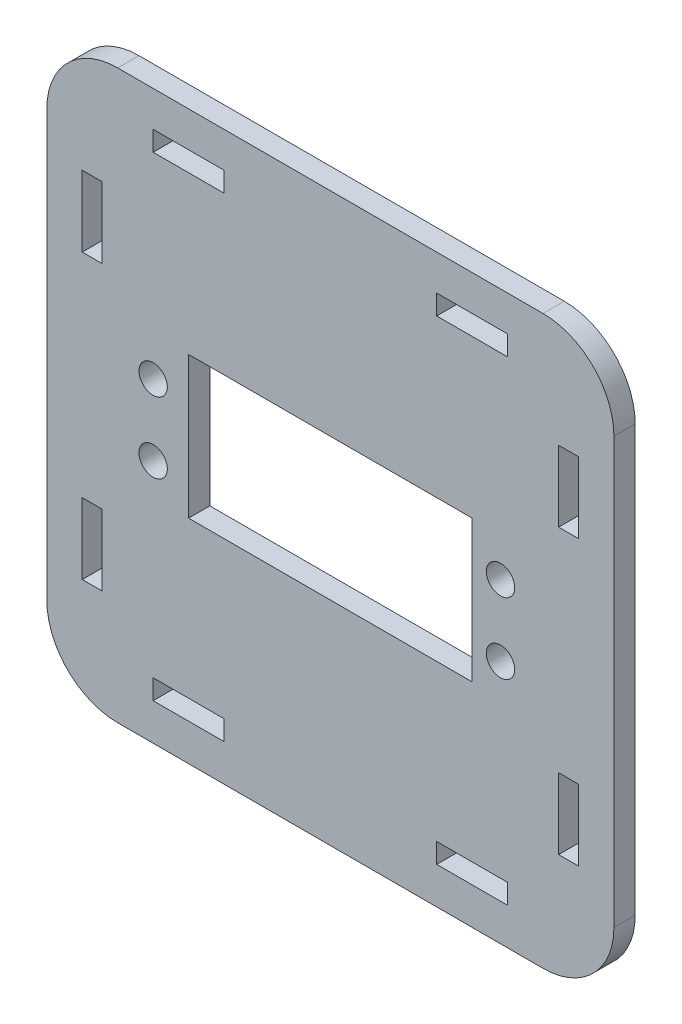
SolidWorks part; units mm, degrees
ref_plane "Plan de face" through (0, 0, 0) normal (0, 0, 1) x (1, 0, 0)
ref_plane "Plan de dessus" through (0, 0, 0) normal (0, 1, 0) x (1, 0, 0)
ref_plane "Plan de droite" through (0, 0, 0) normal (1, 0, 0) x (0, 0, -1)
sketch "Esquisse2" plane through (0, 0, 0) normal (0, 0, 1) x (1, 0, 0)
  line L1 (10, 0) -> (70, 0)
  line L2 (0, 10) -> (0, 70)
  line L3 (10, 80) -> (70, 80)
  line L4 (80, 10) -> (80, 70)
  arc A0 (70, 0) -> (80, 10) centre (70, 10) ccw
  arc A1 (10, 0) -> (0, 10) centre (10, 10) cw
  arc A2 (0, 70) -> (10, 80) centre (10, 70) cw
  arc A3 (70, 80) -> (80, 70) centre (70, 70) cw
  point P11 (0, 0)
  point P14 (0, 80)
  point P17 (80, 80)
  dimension "D3" = 10
  dimension "D1" = 80
  dimension "D2" = 80
extrude "Boss.-Extru.1" add sketch "Esquisse2" along normal blind 3
sketch "Esquisse4" plane through (0, 0, 3) normal (0, 0, 1) x (1, 0, 0)
  line L0 (70, 80) -> (10, 80) construction
  line L1 (65, 75) -> (55, 75)
  line L2 (65, 75) -> (65, 72.2)
  line L3 (65, 72.2) -> (55, 72.2)
  line L4 (55, 75) -> (55, 72.2)
  line L5 (80, 10) -> (80, 70) construction
  line L6 (25, 75) -> (25, 72.2)
  line L7 (25, 75) -> (15, 75)
  line L8 (15, 75) -> (15, 72.2)
  line L9 (25, 72.2) -> (15, 72.2)
  line L10 (25, 8) -> (25, 5.2)
  line L11 (25, 8) -> (15, 8)
  line L12 (15, 8) -> (15, 5.2)
  line L13 (25, 5.2) -> (15, 5.2)
  line L14 (65, 8) -> (65, 5.2)
  line L15 (65, 8) -> (55, 8)
  line L16 (55, 8) -> (55, 5.2)
  line L17 (65, 5.2) -> (55, 5.2)
  line L18 (0, 70) -> (0, 10) construction
  dimension "D1" = 5
  dimension "D2" = 2.8
  dimension "D3" = 10
  dimension "D4" = 15
  dimension "D7" = 15
  dimension "D5" = 2
  dimension "D6" = 2
extrude "Enlèv. mat.-Extru.2" cut sketch "Esquisse4" against normal through all
sketch "Esquisse5" plane through (0, 0, 3) normal (0, 0, 1) x (1, 0, 0)
  line L0 (80, 10) -> (80, 70) construction
  line L1 (75, 65) -> (72.2, 65)
  line L2 (75, 65) -> (75, 55)
  line L3 (75, 55) -> (72.2, 55)
  line L4 (72.2, 65) -> (72.2, 55)
  line L5 (5, 65) -> (7.8, 65)
  line L6 (5, 65) -> (5, 55)
  line L7 (5, 55) -> (7.8, 55)
  line L8 (7.8, 65) -> (7.8, 55)
  line L12 (5, 25) -> (5, 15)
  line L13 (5, 25) -> (7.8, 25)
  line L14 (7.8, 25) -> (7.8, 15)
  line L15 (5, 15) -> (7.8, 15)
  line L16 (75, 25) -> (75, 15)
  line L17 (75, 25) -> (72.2, 25)
  line L18 (72.2, 25) -> (72.2, 15)
  line L19 (75, 15) -> (72.2, 15)
  line L21 (0, 70) -> (0, 10) construction
  line L23 (70, 80) -> (10, 80) construction
  line L24 (10, 0) -> (70, 0) construction
  dimension "D1" = 5
  dimension "D2" = 10
  dimension "D3" = 2.8
  dimension "D4" = 15
  dimension "D5" = 10
  dimension "D6" = 2.8
  dimension "D7" = 15
  dimension "D8" = 5
  dimension "D10" = 15
  dimension "D9" = 2
extrude "Enlèv. mat.-Extru.3" cut sketch "Esquisse5" against normal through all
sketch "Esquisse6" plane through (0, 0, 3) normal (0, 0, 1) x (1, 0, 0)
  line L0 (70, 80) -> (10, 80) construction
  line L1 (20, 50) -> (60, 50)
  line L2 (20, 50) -> (20, 30)
  line L3 (20, 30) -> (60, 30)
  line L4 (60, 50) -> (60, 30)
  line L5 (20, 50) -> (60, 30) construction
  line L6 (20, 30) -> (60, 50) construction
  line L7 (80, 10) -> (80, 70) construction
  point P0 (40, 40)
  dimension "D1" = 40
  dimension "D2" = 20
  dimension "D3" = 40
  dimension "D4" = 40
extrude "Enlèv. mat.-Extru.4" cut sketch "Esquisse6" against normal through all
sketch "Esquisse7" plane through (0, 0, 0) normal (0, 0, -1) x (-1, 0, 0)
  circle A0 centre (-15, 34.5) radius 2
  circle A1 centre (-15, 44.5) radius 2
  circle A2 centre (-64, 34.5) radius 2
  circle A3 centre (-64, 44.5) radius 2
extrude "Enlèv. mat.-Extru.5" cut sketch "Esquisse7" against normal through all
